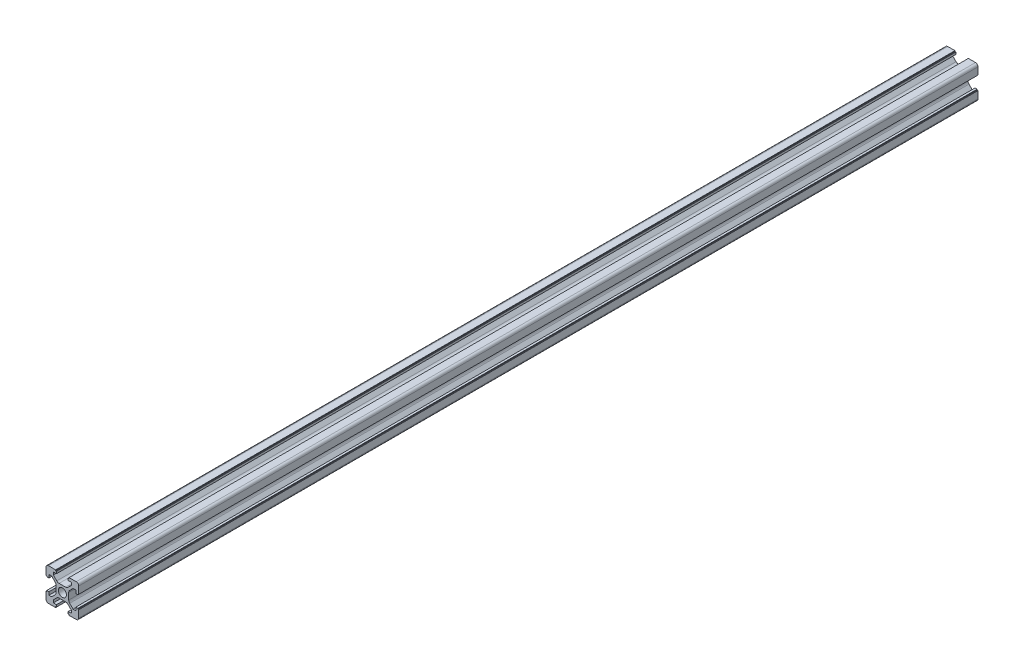
SolidWorks part; units mm, degrees
material "6063-O"
ref_plane "Front Plane" through (0, 0, 0) normal (0, 0, 1) x (1, 0, 0)
ref_plane "Top Plane" through (0, 0, 0) normal (0, 1, 0) x (1, 0, 0)
ref_plane "Right Plane" through (0, 0, 0) normal (1, 0, 0) x (0, 0, -1)
sketch "Sketch1" plane through (0, 0, 0) normal (0, 0, 1) x (1, 0, 0)
  line L0 (10, -4.1) -> (10, -8.5)
  line L1 (4.1, 10) -> (8.5, 10)
  line L2 (8.5, -10) -> (4.1, -10)
  line L3 (-8.5, -10) -> (-4.1, -10)
  line L4 (10, 8.5) -> (10, 4.1)
  line L7 (8.5, 10) -> (4.1, 10)
  line L8 (5.5, 6.5607) -> (3.4251, 4.4858)
  line L9 (8.5, 10) -> (4.1, 10)
  line L10 (3.9, 2.0109) -> (3.9, -2.0109)
  line L11 (2.0109, -3.9) -> (-2.0109, -3.9)
  line L12 (-3.9, -2.0109) -> (-3.9, 2.0109)
  line L13 (-2.0109, 3.9) -> (2.8393, 3.9)
  line L14 (2.5, 0) -> (22.2403, 0) construction
  line L15 (3.6, 9.5) -> (3.6, 8.2)
  line L16 (9.5, 3.6) -> (8.2, 3.6)
  line L17 (8.2, 3.6) -> (8.2, 5.5)
  line L18 (8.2, 5.5) -> (6.5607, 5.5)
  line L19 (10, -4.1) -> (10, -8.5)
  line L20 (4.1, 9.5) -> (3.6, 9.5)
  line L21 (4.1, 10) -> (4.1, 9.5)
  line L22 (8.5, 10) -> (4.1, 10)
  line L23 (10, 4.1) -> (9.5, 4.1)
  line L24 (9.5, 4.1) -> (9.5, 3.6)
  line L25 (5.5, 8.2) -> (5.5, 6.5607)
  line L26 (3.6, 8.2) -> (5.5, 8.2)
  line L27 (4.4858, 3.4251) -> (6.5607, 5.5)
  line L28 (10, -8.5) -> (10, -4.1)
  line L29 (6.5607, -5.5) -> (4.4858, -3.4251)
  line L30 (10, -8.5) -> (10, -4.1)
  line L31 (2.0109, -3.9) -> (-2.0109, -3.9)
  line L32 (3.9, 2.8393) -> (3.9, -2.0109)
  line L33 (9.5, -3.6) -> (8.2, -3.6)
  line L34 (3.6, -9.5) -> (3.6, -8.2)
  line L35 (3.6, -8.2) -> (5.5, -8.2)
  line L36 (5.5, -8.2) -> (5.5, -6.5607)
  line L37 (9.5, -4.1) -> (9.5, -3.6)
  line L38 (10, -4.1) -> (9.5, -4.1)
  line L39 (10, -8.5) -> (10, -4.1)
  line L40 (4.1, -10) -> (4.1, -9.5)
  line L41 (4.1, -9.5) -> (3.6, -9.5)
  line L42 (8.2, -5.5) -> (6.5607, -5.5)
  line L43 (8.2, -3.6) -> (8.2, -5.5)
  line L44 (3.4251, -4.4858) -> (5.5, -6.5607)
  line L45 (-4.1, -10) -> (-8.5, -10)
  line L46 (-10, -8.5) -> (-10, -4.1)
  line L47 (-8.5, -10) -> (-4.1, -10)
  line L48 (-5.5, -6.5607) -> (-3.4251, -4.4858)
  line L49 (-8.5, -10) -> (-4.1, -10)
  line L50 (-3.9, -2.0109) -> (-3.9, 2.0109)
  line L51 (2.0109, -3.9) -> (-2.0109, -3.9)
  line L52 (-3.6, -9.5) -> (-3.6, -8.2)
  line L53 (-9.5, -3.6) -> (-8.2, -3.6)
  line L54 (-8.2, -3.6) -> (-8.2, -5.5)
  line L55 (-8.2, -5.5) -> (-6.5607, -5.5)
  line L56 (-4.1, -9.5) -> (-3.6, -9.5)
  line L57 (-4.1, -10) -> (-4.1, -9.5)
  line L58 (-8.5, -10) -> (-4.1, -10)
  line L59 (-10, -4.1) -> (-9.5, -4.1)
  line L60 (-9.5, -4.1) -> (-9.5, -3.6)
  line L61 (-5.5, -8.2) -> (-5.5, -6.5607)
  line L62 (-3.6, -8.2) -> (-5.5, -8.2)
  line L63 (-4.4858, -3.4251) -> (-6.5607, -5.5)
  line L64 (-10, 4.1) -> (-10, 8.5)
  line L65 (-8.5, 10) -> (-4.1, 10)
  line L66 (-10, 8.5) -> (-10, 4.1)
  line L67 (-6.5607, 5.5) -> (-4.4858, 3.4251)
  line L68 (-10, 8.5) -> (-10, 4.1)
  line L69 (-2.0109, 3.9) -> (2.0109, 3.9)
  line L70 (-3.9, -2.0109) -> (-3.9, 2.0109)
  line L71 (-9.5, 3.6) -> (-8.2, 3.6)
  line L72 (-3.6, 9.5) -> (-3.6, 8.2)
  line L73 (-3.6, 8.2) -> (-5.5, 8.2)
  line L74 (-5.5, 8.2) -> (-5.5, 6.5607)
  line L75 (-9.5, 4.1) -> (-9.5, 3.6)
  line L76 (-10, 4.1) -> (-9.5, 4.1)
  line L77 (-10, 8.5) -> (-10, 4.1)
  line L78 (-4.1, 10) -> (-4.1, 9.5)
  line L79 (-4.1, 9.5) -> (-3.6, 9.5)
  line L80 (-8.2, 5.5) -> (-6.5607, 5.5)
  line L81 (-8.2, 3.6) -> (-8.2, 5.5)
  line L82 (-3.4251, 4.4858) -> (-5.5, 6.5607)
  line L83 (4.1, -10) -> (8.5, -10)
  arc A0 (2.0109, -3.9) -> (3.4251, -4.4858) centre (2.0109, -5.9) cw
  arc A1 (4.4858, -3.4251) -> (3.9, -2.0109) centre (5.9, -2.0109) cw
  arc A2 (3.9, 2.0109) -> (4.4858, 3.4251) centre (5.9, 2.0109) cw
  arc A3 (2.0109, 3.9) -> (3.4251, 4.4858) centre (2.0109, 5.9) ccw
  arc A4 (-2.0109, 3.9) -> (-3.4251, 4.4858) centre (-2.0109, 5.9) cw
  arc A5 (-4.4858, 3.4251) -> (-3.9, 2.0109) centre (-5.9, 2.0109) cw
  arc A6 (-3.4251, -4.4858) -> (-2.0109, -3.9) centre (-2.0109, -5.9) cw
  arc A7 (-3.9, -2.0109) -> (-4.4858, -3.4251) centre (-5.9, -2.0109) cw
  circle A8 centre (0, 0) radius 2.5
  arc A9 (-8.5, -10) -> (-10, -8.5) centre (-8.5, -8.5) cw
  arc A10 (-10, 8.5) -> (-8.5, 10) centre (-8.5, 8.5) cw
  arc A11 (8.5, 10) -> (10, 8.5) centre (8.5, 8.5) cw
  arc A12 (8.5, -10) -> (10, -8.5) centre (8.5, -8.5) ccw
  point P0 (0, 0)
  point P86 (0, 0)
  point P107 (10, -10)
  dimension "D3" = 2
  dimension "D5" = 5
  dimension "D2" = 1.5
  dimension "D8" = 1.5
  dimension "D6" = 4
  dimension "D7" = 6.1
  dimension "D11" = 0.5
  dimension "D12" = 0.5
extrude "Boss-Extrude2" add sketch "Sketch1" along normal blind 550
